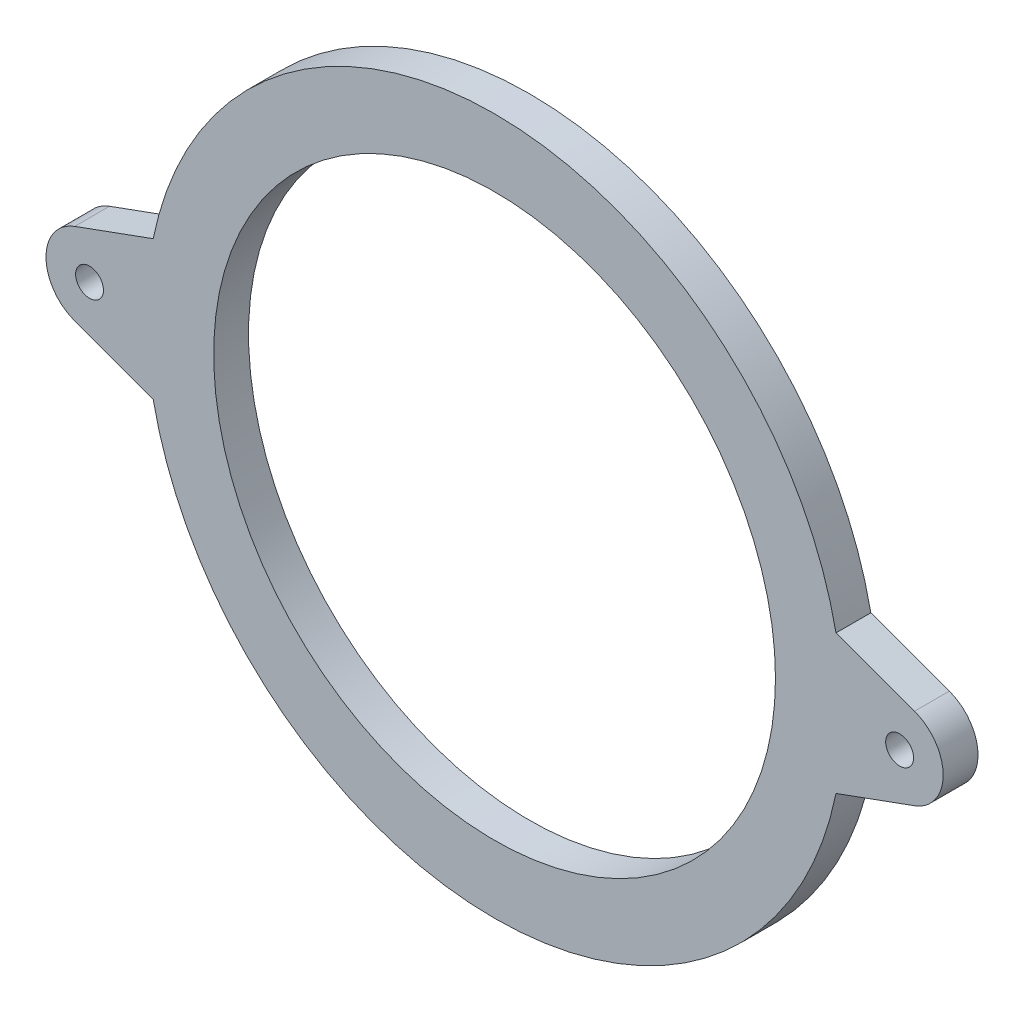
SolidWorks part; units mm, degrees
ref_plane "前视基准面" through (0, 0, 0) normal (0, 0, 1) x (1, 0, 0)
ref_plane "上视基准面" through (0, 0, 0) normal (0, 1, 0) x (1, 0, 0)
ref_plane "右视基准面" through (0, 0, 0) normal (1, 0, 0) x (0, 0, -1)
sketch "草图1" plane through (0, 0, 0) normal (0, 0, 1) x (1, 0, 0)
  circle A0 centre (0, 0) radius 32.25
  circle A1 centre (0, 0) radius 40
  dimension "D1" = 64.5
  dimension "D2" = 80
extrude "凸台-拉伸1" add sketch "草图1" along normal blind 4
sketch "草图2" plane through (0, 0, 0) normal (0, 0, -1) x (-1, 0, 0)
  line L0 (0, 0) -> (46.5, 0) construction
  line L1 (48.2101, 4.6985) -> (39.1961, 7.9793)
  line L2 (48.2101, -4.6985) -> (39.1961, -7.9793)
  line L3 (0, 0) -> (0, 40) construction
  line L4 (0, 0) -> (-46.5, 0) construction
  line L5 (-48.2101, -4.6985) -> (-39.1961, -7.9793)
  line L6 (-48.2101, 4.6985) -> (-39.1961, 7.9793)
  circle A0 centre (46.5, 0) radius 1.6
  arc A1 (48.2101, -4.6985) -> (48.2101, 4.6985) centre (46.5, 0) ccw
  circle A2 centre (0, 0) radius 40 construction
  arc A3 (39.1961, -7.9793) -> (39.1961, 7.9793) centre (0, 0) ccw
  arc A4 (-39.1961, -7.9793) -> (-39.1961, 7.9793) centre (0, 0) cw
  arc A5 (-48.2101, -4.6985) -> (-48.2101, 4.6985) centre (-46.5, 0) cw
  circle A6 centre (-46.5, 0) radius 1.6
  dimension "D1" = 3.2
  dimension "D3" = 10
  dimension "D2" = 46.5
  dimension "D4" = 20
extrude "凸台-拉伸2" add sketch "草图2" against normal up to surface (4 mm away) up to face at (40, 0, 4)
